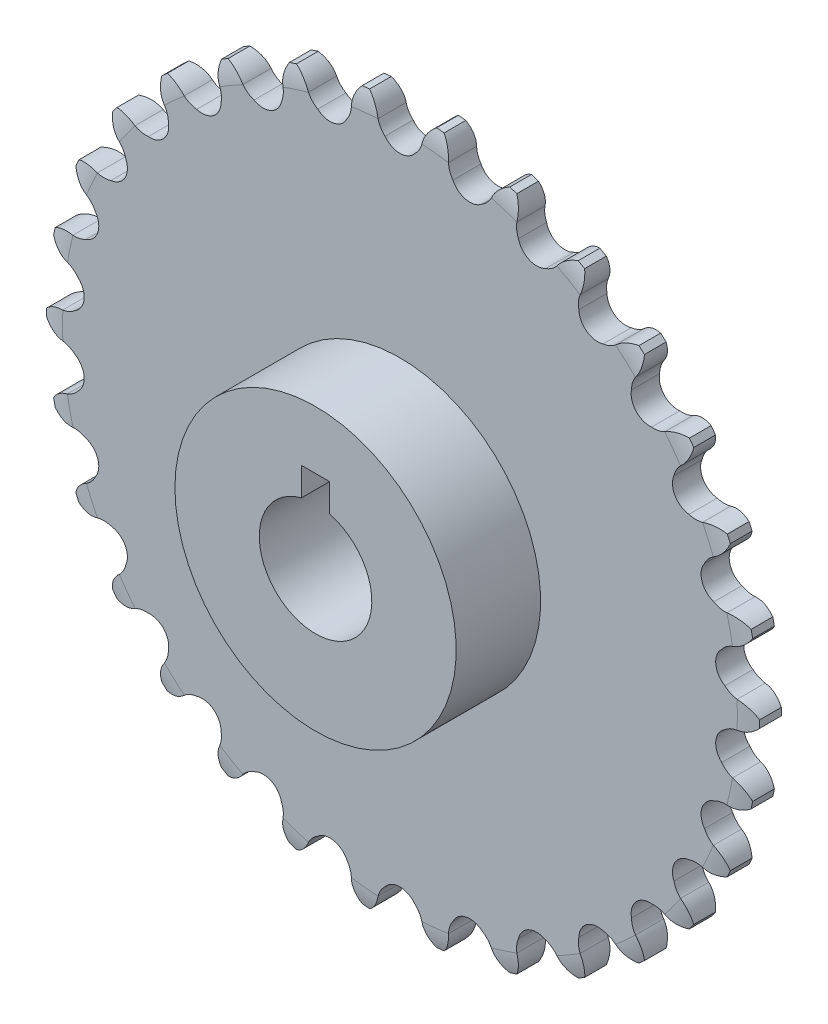
SolidWorks part; units mm, degrees
material "AISI 1035 Steel (SS)"
ref_plane "Front Plane" through (0, 0, 0) normal (0, 0, 1) x (1, 0, 0)
ref_plane "Top Plane" through (0, 0, 0) normal (0, 1, 0) x (1, 0, 0)
ref_plane "Right Plane" through (0, 0, 0) normal (1, 0, 0) x (0, 0, -1)
sketch "Sketch1" plane through (0, 0, 0) normal (0, 0, 1) x (1, 0, 0)
  line L0 (0, 0) -> (0, 151.3586) construction
  line L1 (-78.4621, 30.3746) -> (31.2698, 30.3746) construction
  line L2 (-78.4621, 31.9646) -> (82.3059, 31.9646) construction
  line L3 (2.1107, 0) -> (2.1107, 151.3586) construction
  line L4 (2.1107, 31.9646) -> (-1.3548, 29.3531)
  line L5 (2.1107, 31.9646) -> (-1.9802, 30.4052)
  line L6 (-78.4621, 30.3746) -> (82.3059, 30.3746) construction
  line L7 (-4.5974, 0) -> (-4.5974, 151.3586) construction
  line L8 (-78.4621, 29.892) -> (82.3059, 29.892) construction
  line L9 (0, 0) -> (-3.9581, 37.6587) construction
  circle A0 centre (0, 0) radius 30.3746 construction
  arc A4 (-1.9802, 30.4052) -> (-1.3548, 29.3531) centre (0.1213, 30.9426) ccw
  arc A6 (-1.9802, 30.4052) -> (-3.3918, 32.2709) centre (-4.5974, 29.892) ccw
  arc A7 (-1.3548, 29.3531) -> (1.3548, 29.3531) centre (0, 30.3746) ccw
  arc A8 (1.9802, 30.4052) -> (3.3918, 32.2709) centre (4.5974, 29.892) cw
  arc A9 (1.9802, 30.4052) -> (1.3548, 29.3531) centre (-0.1213, 30.9426) cw
  arc A10 (4.3846, 30.1525) -> (3.3918, 32.2709) centre (1.718, 30.1946) ccw
  arc A11 (4.3846, 30.1525) -> (4.7777, 28.9934) centre (6.552, 30.2412) ccw
  arc A12 (4.7777, 28.9934) -> (7.4281, 28.43) centre (6.3152, 29.7108) ccw
  arc A13 (8.2586, 29.329) -> (7.4281, 28.43) centre (6.3147, 30.2917) cw
  arc A14 (8.2586, 29.329) -> (10.0272, 30.8606) centre (10.7118, 28.2829) cw
  arc A15 (10.5579, 28.5819) -> (10.0272, 30.8606) centre (7.9582, 29.1776) ccw
  arc A16 (10.5579, 28.5819) -> (10.7013, 27.3665) centre (12.6963, 28.2181) ccw
  arc A17 (10.7013, 27.3665) -> (13.1767, 26.2644) centre (12.3545, 27.7486) ccw
  arc A18 (14.1759, 26.9711) -> (13.1767, 26.2644) centre (12.4747, 28.3168) cw
  arc A19 (14.1759, 26.9711) -> (16.2244, 28.1014) centre (16.3581, 25.4378) cw
  arc A20 (16.2697, 25.7622) -> (16.2244, 28.1014) centre (13.8507, 26.8854) ccw
  arc A21 (16.2697, 25.7622) -> (16.1573, 24.5435) centre (18.2857, 24.9618) ccw
  arc A22 (16.1573, 24.5435) -> (18.3494, 22.9509) centre (17.8537, 24.5736) ccw
  arc A23 (19.4738, 23.4343) -> (18.3494, 22.9509) centre (18.0895, 25.1044) cw
  arc A24 (19.4738, 23.4343) -> (21.7124, 24.1141) centre (21.2894, 21.4808) cw
  arc A25 (21.2704, 21.8166) -> (21.7124, 24.1141) centre (19.1378, 23.4182) ccw
  arc A26 (21.2704, 21.8166) -> (20.9071, 20.6479) centre (23.076, 20.6145) ccw
  arc A27 (20.9071, 20.6479) -> (22.7202, 18.6343) centre (22.5727, 20.3246) ccw
  arc A28 (23.9205, 18.8734) -> (22.7202, 18.6343) centre (22.9137, 20.7948) cw
  arc A29 (23.9205, 18.8734) -> (26.2516, 19.0729) centre (25.2903, 16.5851) cw
  arc A30 (25.3415, 16.9175) -> (26.2516, 19.0729) centre (23.5885, 18.9275) ccw
  arc A31 (25.3415, 16.9175) -> (24.7432, 15.8499) centre (26.8577, 15.3663) ccw
  arc A32 (24.7432, 15.8499) -> (26.098, 13.5033) centre (26.3052, 15.1873) ccw
  arc A33 (27.3218, 13.4876) -> (26.098, 13.5033) centre (26.7364, 15.5763) cw
  arc A34 (27.3218, 13.4876) -> (29.6434, 13.1981) centre (28.1859, 10.9645) cw
  arc A35 (28.3051, 11.279) -> (29.6434, 13.1981) centre (27.0083, 13.6095) ccw
  arc A36 (28.3051, 11.279) -> (27.4978, 10.3591) centre (29.4656, 9.4464) ccw
  arc A37 (27.4978, 10.3591) -> (28.3352, 7.7821) centre (28.888, 9.3863) ccw
  arc A38 (29.529, 7.5124) -> (28.3352, 7.7821) centre (29.3907, 9.6771) cw
  arc A39 (29.529, 7.5124) -> (31.7396, 6.7465) centre (29.8496, 4.8647) cw
  arc A40 (30.0316, 5.1476) -> (31.7396, 6.7465) centre (29.2477, 7.6968) ccw
  arc A41 (30.0316, 5.1476) -> (29.0507, 4.4156) centre (30.7858, 3.1138) ccw
  arc A42 (29.0507, 4.4156) -> (29.334, 1.7208) centre (30.2082, 3.175) ccw
  arc A43 (30.4456, 1.2088) -> (29.334, 1.7208) centre (30.7604, 3.355) cw
  arc A44 (30.4456, 1.2088) -> (32.4487, 0) centre (30.2088, -1.4477) cw
  arc A45 (30.4456, -1.2088) -> (32.4487, 0) centre (30.2088, 1.4477) ccw
  arc A46 (30.4456, -1.2088) -> (29.334, -1.7208) centre (30.7604, -3.355) ccw
  arc A47 (29.334, -1.7208) -> (29.0507, -4.4156) centre (30.2082, -3.175) ccw
  arc A48 (30.0316, -5.1476) -> (29.0507, -4.4156) centre (30.7858, -3.1138) cw
  arc A49 (30.0316, -5.1476) -> (31.7396, -6.7465) centre (29.2477, -7.6968) cw
  arc A50 (29.529, -7.5124) -> (31.7396, -6.7465) centre (29.8496, -4.8647) ccw
  arc A51 (29.529, -7.5124) -> (28.3352, -7.7821) centre (29.3907, -9.6771) ccw
  arc A52 (28.3352, -7.7821) -> (27.4978, -10.3591) centre (28.888, -9.3863) ccw
  arc A53 (28.3051, -11.279) -> (27.4978, -10.3591) centre (29.4656, -9.4464) cw
  arc A54 (28.3051, -11.279) -> (29.6434, -13.1981) centre (27.0083, -13.6095) cw
  arc A55 (27.3218, -13.4876) -> (29.6434, -13.1981) centre (28.1859, -10.9645) ccw
  arc A56 (27.3218, -13.4876) -> (26.098, -13.5033) centre (26.7364, -15.5763) ccw
  arc A57 (26.098, -13.5033) -> (24.7432, -15.8499) centre (26.3052, -15.1873) ccw
  arc A58 (25.3415, -16.9175) -> (24.7432, -15.8499) centre (26.8577, -15.3663) cw
  arc A59 (25.3415, -16.9175) -> (26.2516, -19.0729) centre (23.5885, -18.9275) cw
  arc A60 (23.9205, -18.8734) -> (26.2516, -19.0729) centre (25.2903, -16.5851) ccw
  arc A61 (23.9205, -18.8734) -> (22.7202, -18.6343) centre (22.9137, -20.7948) ccw
  arc A62 (22.7202, -18.6343) -> (20.9071, -20.6479) centre (22.5727, -20.3246) ccw
  arc A63 (21.2704, -21.8166) -> (20.9071, -20.6479) centre (23.076, -20.6145) cw
  arc A64 (21.2704, -21.8166) -> (21.7124, -24.1141) centre (19.1378, -23.4182) cw
  arc A65 (19.4738, -23.4343) -> (21.7124, -24.1141) centre (21.2894, -21.4808) ccw
  arc A66 (19.4738, -23.4343) -> (18.3494, -22.9509) centre (18.0895, -25.1044) ccw
  arc A67 (18.3494, -22.9509) -> (16.1573, -24.5435) centre (17.8537, -24.5736) ccw
  arc A68 (16.2697, -25.7622) -> (16.1573, -24.5435) centre (18.2857, -24.9618) cw
  arc A69 (16.2697, -25.7622) -> (16.2244, -28.1014) centre (13.8507, -26.8854) cw
  arc A70 (14.1759, -26.9711) -> (16.2244, -28.1014) centre (16.3581, -25.4378) ccw
  arc A71 (14.1759, -26.9711) -> (13.1767, -26.2644) centre (12.4747, -28.3168) ccw
  arc A72 (13.1767, -26.2644) -> (10.7013, -27.3665) centre (12.3545, -27.7486) ccw
  arc A73 (10.5579, -28.5819) -> (10.7013, -27.3665) centre (12.6963, -28.2181) cw
  arc A74 (10.5579, -28.5819) -> (10.0272, -30.8606) centre (7.9582, -29.1776) cw
  arc A75 (8.2586, -29.329) -> (10.0272, -30.8606) centre (10.7118, -28.2829) ccw
  arc A76 (8.2586, -29.329) -> (7.4281, -28.43) centre (6.3147, -30.2917) ccw
  arc A77 (7.4281, -28.43) -> (4.7777, -28.9934) centre (6.3152, -29.7108) ccw
  arc A78 (4.3846, -30.1525) -> (4.7777, -28.9934) centre (6.552, -30.2412) cw
  arc A79 (4.3846, -30.1525) -> (3.3918, -32.2709) centre (1.718, -30.1946) cw
  arc A80 (1.9802, -30.4052) -> (3.3918, -32.2709) centre (4.5974, -29.892) ccw
  arc A81 (1.9802, -30.4052) -> (1.3548, -29.3531) centre (-0.1213, -30.9426) ccw
  arc A82 (1.3548, -29.3531) -> (-1.3548, -29.3531) centre (0, -30.3746) ccw
  arc A83 (-1.9802, -30.4052) -> (-1.3548, -29.3531) centre (0.1213, -30.9426) cw
  arc A84 (-1.9802, -30.4052) -> (-3.3918, -32.2709) centre (-4.5974, -29.892) cw
  arc A85 (-4.3846, -30.1525) -> (-3.3918, -32.2709) centre (-1.718, -30.1946) ccw
  arc A86 (-4.3846, -30.1525) -> (-4.7777, -28.9934) centre (-6.552, -30.2412) ccw
  arc A87 (-4.7777, -28.9934) -> (-7.4281, -28.43) centre (-6.3152, -29.7108) ccw
  arc A88 (-8.2586, -29.329) -> (-7.4281, -28.43) centre (-6.3147, -30.2917) cw
  arc A89 (-8.2586, -29.329) -> (-10.0272, -30.8606) centre (-10.7118, -28.2829) cw
  arc A90 (-10.5579, -28.5819) -> (-10.0272, -30.8606) centre (-7.9582, -29.1776) ccw
  arc A91 (-10.5579, -28.5819) -> (-10.7013, -27.3665) centre (-12.6963, -28.2181) ccw
  arc A92 (-10.7013, -27.3665) -> (-13.1767, -26.2644) centre (-12.3545, -27.7486) ccw
  arc A93 (-14.1759, -26.9711) -> (-13.1767, -26.2644) centre (-12.4747, -28.3168) cw
  arc A94 (-14.1759, -26.9711) -> (-16.2244, -28.1014) centre (-16.3581, -25.4378) cw
  arc A95 (-16.2697, -25.7622) -> (-16.2244, -28.1014) centre (-13.8507, -26.8854) ccw
  arc A96 (-16.2697, -25.7622) -> (-16.1573, -24.5435) centre (-18.2857, -24.9618) ccw
  arc A97 (-16.1573, -24.5435) -> (-18.3494, -22.9509) centre (-17.8537, -24.5736) ccw
  arc A98 (-19.4738, -23.4343) -> (-18.3494, -22.9509) centre (-18.0895, -25.1044) cw
  arc A99 (-19.4738, -23.4343) -> (-21.7124, -24.1141) centre (-21.2894, -21.4808) cw
  arc A100 (-21.2704, -21.8166) -> (-21.7124, -24.1141) centre (-19.1378, -23.4182) ccw
  arc A101 (-21.2704, -21.8166) -> (-20.9071, -20.6479) centre (-23.076, -20.6145) ccw
  arc A102 (-20.9071, -20.6479) -> (-22.7202, -18.6343) centre (-22.5727, -20.3246) ccw
  arc A103 (-23.9205, -18.8734) -> (-22.7202, -18.6343) centre (-22.9137, -20.7948) cw
  arc A104 (-23.9205, -18.8734) -> (-26.2516, -19.0729) centre (-25.2903, -16.5851) cw
  arc A105 (-25.3415, -16.9175) -> (-26.2516, -19.0729) centre (-23.5885, -18.9275) ccw
  arc A106 (-25.3415, -16.9175) -> (-24.7432, -15.8499) centre (-26.8577, -15.3663) ccw
  arc A107 (-24.7432, -15.8499) -> (-26.098, -13.5033) centre (-26.3052, -15.1873) ccw
  arc A108 (-27.3218, -13.4876) -> (-26.098, -13.5033) centre (-26.7364, -15.5763) cw
  arc A109 (-27.3218, -13.4876) -> (-29.6434, -13.1981) centre (-28.1859, -10.9645) cw
  arc A110 (-28.3051, -11.279) -> (-29.6434, -13.1981) centre (-27.0083, -13.6095) ccw
  arc A111 (-28.3051, -11.279) -> (-27.4978, -10.3591) centre (-29.4656, -9.4464) ccw
  arc A112 (-27.4978, -10.3591) -> (-28.3352, -7.7821) centre (-28.888, -9.3863) ccw
  arc A113 (-29.529, -7.5124) -> (-28.3352, -7.7821) centre (-29.3907, -9.6771) cw
  arc A114 (-29.529, -7.5124) -> (-31.7396, -6.7465) centre (-29.8496, -4.8647) cw
  arc A115 (-30.0316, -5.1476) -> (-31.7396, -6.7465) centre (-29.2477, -7.6968) ccw
  arc A116 (-30.0316, -5.1476) -> (-29.0507, -4.4156) centre (-30.7858, -3.1138) ccw
  arc A117 (-29.0507, -4.4156) -> (-29.334, -1.7208) centre (-30.2082, -3.175) ccw
  arc A118 (-30.4456, -1.2088) -> (-29.334, -1.7208) centre (-30.7604, -3.355) cw
  arc A119 (-30.4456, -1.2088) -> (-32.4487, 0) centre (-30.2088, 1.4477) cw
  arc A120 (-30.4456, 1.2088) -> (-32.4487, 0) centre (-30.2088, -1.4477) ccw
  arc A121 (-30.4456, 1.2088) -> (-29.334, 1.7208) centre (-30.7604, 3.355) ccw
  arc A122 (-29.334, 1.7208) -> (-29.0507, 4.4156) centre (-30.2082, 3.175) ccw
  arc A123 (-30.0316, 5.1476) -> (-29.0507, 4.4156) centre (-30.7858, 3.1138) cw
  arc A124 (-30.0316, 5.1476) -> (-31.7396, 6.7465) centre (-29.2477, 7.6968) cw
  arc A125 (-29.529, 7.5124) -> (-31.7396, 6.7465) centre (-29.8496, 4.8647) ccw
  arc A126 (-29.529, 7.5124) -> (-28.3352, 7.7821) centre (-29.3907, 9.6771) ccw
  arc A127 (-28.3352, 7.7821) -> (-27.4978, 10.3591) centre (-28.888, 9.3863) ccw
  arc A128 (-28.3051, 11.279) -> (-27.4978, 10.3591) centre (-29.4656, 9.4464) cw
  arc A129 (-28.3051, 11.279) -> (-29.6434, 13.1981) centre (-27.0083, 13.6095) cw
  arc A130 (-27.3218, 13.4876) -> (-29.6434, 13.1981) centre (-28.1859, 10.9645) ccw
  arc A131 (-27.3218, 13.4876) -> (-26.098, 13.5033) centre (-26.7364, 15.5763) ccw
  arc A132 (-26.098, 13.5033) -> (-24.7432, 15.8499) centre (-26.3052, 15.1873) ccw
  arc A133 (-25.3415, 16.9175) -> (-24.7432, 15.8499) centre (-26.8577, 15.3663) cw
  arc A134 (-25.3415, 16.9175) -> (-26.2516, 19.0729) centre (-23.5885, 18.9275) cw
  arc A135 (-23.9205, 18.8734) -> (-26.2516, 19.0729) centre (-25.2903, 16.5851) ccw
  arc A136 (-23.9205, 18.8734) -> (-22.7202, 18.6343) centre (-22.9137, 20.7948) ccw
  arc A137 (-22.7202, 18.6343) -> (-20.9071, 20.6479) centre (-22.5727, 20.3246) ccw
  arc A138 (-21.2704, 21.8166) -> (-20.9071, 20.6479) centre (-23.076, 20.6145) cw
  arc A139 (-21.2704, 21.8166) -> (-21.7124, 24.1141) centre (-19.1378, 23.4182) cw
  arc A140 (-19.4738, 23.4343) -> (-21.7124, 24.1141) centre (-21.2894, 21.4808) ccw
  arc A141 (-19.4738, 23.4343) -> (-18.3494, 22.9509) centre (-18.0895, 25.1044) ccw
  arc A142 (-18.3494, 22.9509) -> (-16.1573, 24.5435) centre (-17.8537, 24.5736) ccw
  arc A143 (-16.2697, 25.7622) -> (-16.1573, 24.5435) centre (-18.2857, 24.9618) cw
  arc A144 (-16.2697, 25.7622) -> (-16.2244, 28.1014) centre (-13.8507, 26.8854) cw
  arc A145 (-14.1759, 26.9711) -> (-16.2244, 28.1014) centre (-16.3581, 25.4378) ccw
  arc A146 (-14.1759, 26.9711) -> (-13.1767, 26.2644) centre (-12.4747, 28.3168) ccw
  arc A147 (-13.1767, 26.2644) -> (-10.7013, 27.3665) centre (-12.3545, 27.7486) ccw
  arc A148 (-10.5579, 28.5819) -> (-10.7013, 27.3665) centre (-12.6963, 28.2181) cw
  arc A149 (-10.5579, 28.5819) -> (-10.0272, 30.8606) centre (-7.9582, 29.1776) cw
  arc A150 (-8.2586, 29.329) -> (-10.0272, 30.8606) centre (-10.7118, 28.2829) ccw
  arc A151 (-8.2586, 29.329) -> (-7.4281, 28.43) centre (-6.3147, 30.2917) ccw
  arc A152 (-7.4281, 28.43) -> (-4.7777, 28.9934) centre (-6.3152, 29.7108) ccw
  arc A153 (-4.3846, 30.1525) -> (-4.7777, 28.9934) centre (-6.552, 30.2412) cw
  arc A154 (-4.3846, 30.1525) -> (-3.3918, 32.2709) centre (-1.718, 30.1946) cw
  dimension "D1" = 60.7492
  dimension "D2" = 1.6967
  dimension "D7" = 4.3383
  dimension "D10" = 2.667
  dimension "D5" = 37
  dimension "D6" = 16.133
  dimension "D11" = 6
  dimension "D13" = 6.35
  dimension "D3" = 1.59
  dimension "D4" = 2.1107
  dimension "D8" = 4.5974
  dimension "D9" = 0.4826
  dimension "D12" = 30
extrude "Boss-Extrude1" add sketch "Sketch1" along normal mid plane 2.54 contours A154 A153 A152 A151 A150 A149 A148 A147 A146 A145 A144 A143 A142 A141 A140 A139 A138 A137 A136 A135 A134 A133 A132 A131 A130 A129 A128 A127 A126 A125 A124 A123 A122 A121 A120 A119 A118 A117 A116 A115 A114 A113 A112 A111 A110 A109 A108 A107 A106 A105 A104
sketch "Sketch2" plane through (0, 0, 1.27) normal (0, 0, 1) x (1, 0, 0)
  circle A0 centre (0, 0) radius 12.7
  dimension "D1" = 25.4
extrude "Boss-Extrude2" add sketch "Sketch2" along normal blind 7.62
sketch "Sketch3" plane through (0, 0, 8.89) normal (0, 0, 1) x (1, 0, 0)
  line L0 (0, 4.445) -> (0, 6.985) construction
  line L7 (1.27, 4.9187) -> (1.27, 7.4587)
  line L8 (-1.27, 4.9187) -> (-1.27, 7.4587)
  line L9 (1.27, 7.4587) -> (-1.27, 7.4587)
  arc A0 (-1.27, 4.9187) -> (1.27, 4.9187) centre (0, 0) ccw
  dimension "D1" = 10.16
  dimension "D2" = 2.54
  dimension "D3" = 1.27
extrude "Cut-Extrude1" cut sketch "Sketch3" against normal through all
sketch "Sketch4" plane through (0, 0, 0) normal (1, 0, 0) x (0, 0, -1)
  line L0 (1.27, 0) -> (20.2253, 0) construction
  line L1 (-1.27, 32.6977) -> (-1.27, 30.463)
  line L2 (-1.27, 30.8606) -> (-1.27, 28.5819) construction
  line L3 (-1.27, 32.6977) -> (-0.7982, 32.6977)
  line L4 (0, 32.2709) -> (0, 31.4532) construction
  line L5 (-1.27, 32.2709) -> (1.27, 32.2709) construction
  line L6 (1.27, 32.6977) -> (0.7982, 32.6977)
  line L7 (1.27, 32.6977) -> (1.27, 30.463)
  arc A0 (-0.7982, 32.6977) -> (-1.27, 30.463) centre (5.0776, 30.2901) ccw
  arc A1 (0.7982, 32.6977) -> (1.27, 30.463) centre (-5.0776, 30.2901) cw
  dimension "D1" = 12.7
  dimension "D2" = 32.6977
  dimension "D3" = 0.4718
  dimension "D4" = 2.2346
revolve "Cut-Revolve1" cut sketch "Sketch4" angle 360 about L0
sketch "Sketch5" plane through (0, 0, 1.27) normal (0, 0, 1) x (1, 0, 0)
  line L0 (3.3653, 32.0183) -> (3.3918, 32.2709)
  circle A0 centre (0, 0) radius 32.1947
  dimension "D1" = 0.254
extrude "Cut-Extrude2" cut sketch "Sketch5" along normal through all both and the other way through all flip side to cut contours A0
